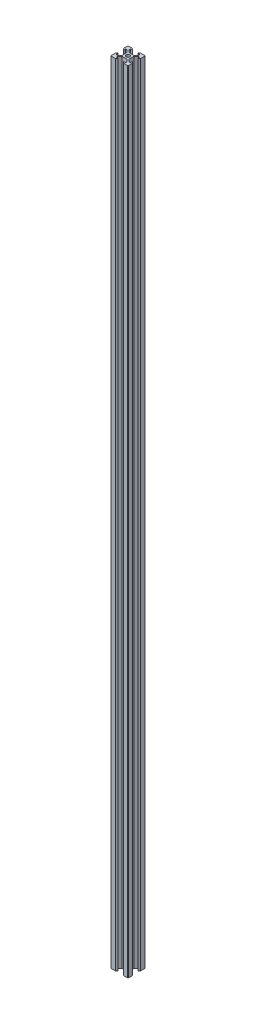
SolidWorks part; units mm, degrees
ref_plane "Front Plane" through (0, 0, 0) normal (0, 0, 1) x (1, 0, 0)
ref_plane "Top Plane" through (0, 0, 0) normal (0, 1, 0) x (1, 0, 0)
ref_plane "Right Plane" through (0, 0, 0) normal (1, 0, 0) x (0, 0, -1)
sketch "Sketch1" plane through (0, 0, 0) normal (1, 0, 0) x (0, 0, -1)
  line L0 (0, 0) -> (0, 914.4)
  dimension "D1" = 914.4
other "Vslot2020 2020(5)"
ref_plane "Plane5" through (0, 0, 0) normal (0, 1, 0) x (0, 0, 1)
sketch "Sketch2" plane through (0, 0, 0) normal (0, 1, 0) x (0, 0, 1)
  line L58 (13.9, 7.1491) -> (13.9, 12.8445)
  line L59 (13.9, 12.8445) -> (16.5585, 15.4922)
  line L60 (16.5585, 15.4922) -> (16.5507, 15.5)
  line L61 (16.5507, 15.5) -> (18.2, 15.5)
  line L62 (18.2, 15.5) -> (18.2, 13.12)
  line L63 (18.2, 13.12) -> (18.5344, 13.12)
  line L64 (18.5344, 13.12) -> (20, 14.58)
  line L65 (20, 14.58) -> (20, 19.5)
  line L66 (19.5, 20) -> (14.575, 20)
  line L67 (14.575, 20) -> (13.12, 18.545)
  line L68 (13.12, 18.545) -> (13.12, 18.2)
  line L69 (13.12, 18.2) -> (15.5, 18.2)
  line L70 (15.5, 18.2) -> (15.5, 16.555)
  line L71 (15.5, 16.555) -> (12.8341, 13.9)
  line L72 (12.8341, 13.9) -> (7.155, 13.9)
  line L73 (7.155, 13.9) -> (4.5, 16.555)
  line L74 (4.5, 16.555) -> (4.5, 18.2)
  line L75 (4.5, 18.2) -> (6.875, 18.2)
  line L76 (6.875, 18.2) -> (6.875, 18.545)
  line L77 (6.875, 18.545) -> (5.42, 20)
  line L78 (5.42, 20) -> (0.5, 20)
  line L79 (0, 19.5) -> (0, 14.58)
  line L80 (0, 14.58) -> (1.46, 13.12)
  line L81 (1.46, 13.12) -> (1.8, 13.12)
  line L82 (1.8, 13.12) -> (1.8, 15.5)
  line L83 (1.8, 15.5) -> (3.445, 15.5)
  line L84 (3.445, 15.5) -> (3.4393, 15.4943)
  line L85 (3.4393, 15.4943) -> (6.0943, 12.8393)
  line L86 (6.0943, 12.8393) -> (6.1, 12.845)
  line L87 (6.1, 12.845) -> (6.1, 7.1491)
  line L88 (6.1, 7.1491) -> (3.4393, 4.5)
  line L89 (3.4393, 4.5) -> (1.8, 4.5)
  line L90 (1.8, 4.5) -> (1.8, 6.88)
  line L91 (1.8, 6.88) -> (1.46, 6.88)
  line L92 (1.46, 6.88) -> (0, 5.42)
  line L93 (0, 5.42) -> (0, 0.5)
  line L94 (0.5, 0) -> (5.42, 0)
  line L95 (5.42, 0) -> (6.875, 1.455)
  line L96 (6.875, 1.455) -> (6.875, 1.8)
  line L97 (6.875, 1.8) -> (4.5, 1.8)
  line L98 (4.5, 1.8) -> (4.5, 3.4393)
  line L99 (4.5, 3.4393) -> (7.1583, 6.0861)
  line L100 (7.1583, 6.0861) -> (7.1445, 6.1)
  line L101 (7.1445, 6.1) -> (12.8546, 6.1)
  line L102 (12.8546, 6.1) -> (12.8412, 6.0865)
  line L103 (12.8412, 6.0865) -> (15.4997, 3.4375)
  line L104 (15.4997, 3.4375) -> (15.5, 3.4377)
  line L105 (15.5, 3.4377) -> (15.5, 1.8)
  line L106 (15.5, 1.8) -> (13.12, 1.8)
  line L107 (13.12, 1.8) -> (13.12, 1.455)
  line L108 (13.12, 1.455) -> (14.575, 0)
  line L109 (14.575, 0) -> (19.5, 0)
  line L110 (20, 0.5) -> (20, 5.42)
  line L111 (20, 5.42) -> (18.6069, 6.88)
  line L112 (18.6069, 6.88) -> (18.2, 6.88)
  line L113 (18.2, 6.88) -> (18.2, 4.5)
  line L114 (18.2, 4.5) -> (16.5585, 4.5)
  line L115 (16.5585, 4.5) -> (13.9, 7.1491)
  line L116 (13.9, 7.1491) -> (13.9, 12.8445)
  line L117 (13.9, 12.8445) -> (16.5585, 15.4922)
  line L118 (16.5585, 15.4922) -> (16.5507, 15.5)
  line L119 (16.5507, 15.5) -> (18.2, 15.5)
  line L120 (18.2, 15.5) -> (18.2, 13.12)
  line L121 (18.2, 13.12) -> (18.5344, 13.12)
  line L122 (18.5344, 13.12) -> (20, 14.58)
  line L123 (20, 14.58) -> (20, 19.5)
  line L124 (19.5, 20) -> (14.575, 20)
  line L125 (14.575, 20) -> (13.12, 18.545)
  line L126 (13.12, 18.545) -> (13.12, 18.2)
  line L127 (13.12, 18.2) -> (15.5, 18.2)
  line L128 (15.5, 18.2) -> (15.5, 16.555)
  line L129 (15.5, 16.555) -> (12.8341, 13.9)
  line L130 (12.8341, 13.9) -> (7.155, 13.9)
  line L131 (7.155, 13.9) -> (4.5, 16.555)
  line L132 (4.5, 16.555) -> (4.5, 18.2)
  line L133 (4.5, 18.2) -> (6.875, 18.2)
  line L134 (6.875, 18.2) -> (6.875, 18.545)
  line L135 (6.875, 18.545) -> (5.42, 20)
  line L136 (5.42, 20) -> (0.5, 20)
  line L137 (0, 19.5) -> (0, 14.58)
  line L138 (0, 14.58) -> (1.46, 13.12)
  line L139 (1.46, 13.12) -> (1.8, 13.12)
  line L140 (1.8, 13.12) -> (1.8, 15.5)
  line L141 (1.8, 15.5) -> (3.445, 15.5)
  line L142 (3.445, 15.5) -> (3.4393, 15.4943)
  line L143 (3.4393, 15.4943) -> (6.0943, 12.8393)
  line L144 (6.0943, 12.8393) -> (6.1, 12.845)
  line L145 (6.1, 12.845) -> (6.1, 7.1491)
  line L146 (6.1, 7.1491) -> (3.4393, 4.5)
  line L147 (3.4393, 4.5) -> (1.8, 4.5)
  line L148 (1.8, 4.5) -> (1.8, 6.88)
  line L149 (1.8, 6.88) -> (1.46, 6.88)
  line L150 (1.46, 6.88) -> (0, 5.42)
  line L151 (0, 5.42) -> (0, 0.5)
  line L152 (0.5, 0) -> (5.42, 0)
  line L153 (5.42, 0) -> (6.875, 1.455)
  line L154 (6.875, 1.455) -> (6.875, 1.8)
  line L155 (6.875, 1.8) -> (4.5, 1.8)
  line L156 (4.5, 1.8) -> (4.5, 3.4393)
  line L157 (4.5, 3.4393) -> (7.1583, 6.0861)
  line L158 (7.1583, 6.0861) -> (7.1445, 6.1)
  line L159 (7.1445, 6.1) -> (12.8546, 6.1)
  line L160 (12.8546, 6.1) -> (12.8412, 6.0865)
  line L161 (12.8412, 6.0865) -> (15.4997, 3.4375)
  line L162 (15.4997, 3.4375) -> (15.5, 3.4377)
  line L163 (15.5, 3.4377) -> (15.5, 1.8)
  line L164 (15.5, 1.8) -> (13.12, 1.8)
  line L165 (13.12, 1.8) -> (13.12, 1.455)
  line L166 (13.12, 1.455) -> (14.575, 0)
  line L167 (14.575, 0) -> (19.5, 0)
  line L168 (20, 0.5) -> (20, 5.42)
  line L169 (20, 5.42) -> (18.6069, 6.88)
  line L170 (18.6069, 6.88) -> (18.2, 6.88)
  line L171 (18.2, 6.88) -> (18.2, 4.5)
  line L172 (18.2, 4.5) -> (16.5585, 4.5)
  line L173 (16.5585, 4.5) -> (13.9, 7.1491)
  circle A0 centre (10, 10) radius 2.0746 construction
  circle A1 centre (10, 10) radius 2.0746
  arc A4 (20, 19.5) -> (19.5, 20) centre (19.5, 19.5) ccw
  arc A5 (0.5, 20) -> (0, 19.5) centre (0.5, 19.5) ccw
  arc A6 (0, 0.5) -> (0.5, 0) centre (0.5, 0.5) ccw
  arc A7 (19.5, 0) -> (20, 0.5) centre (19.5, 0.5) ccw
  arc A8 (20, 19.5) -> (19.5, 20) centre (19.5, 19.5) ccw
  arc A9 (0.5, 20) -> (0, 19.5) centre (0.5, 19.5) ccw
  arc A10 (0, 0.5) -> (0.5, 0) centre (0.5, 0.5) ccw
  arc A11 (19.5, 0) -> (20, 0.5) centre (19.5, 0.5) ccw
  point P16 (0, 0)
  dimension "D1" = 0
ref_plane "Plane6" through (0, 0, 9.9946) normal (0, 0, 1) x (1, 0, 0)
ref_plane "Plane7" through (9.997, 0, 0) normal (1, 0, 0) x (0, 0, -1)
